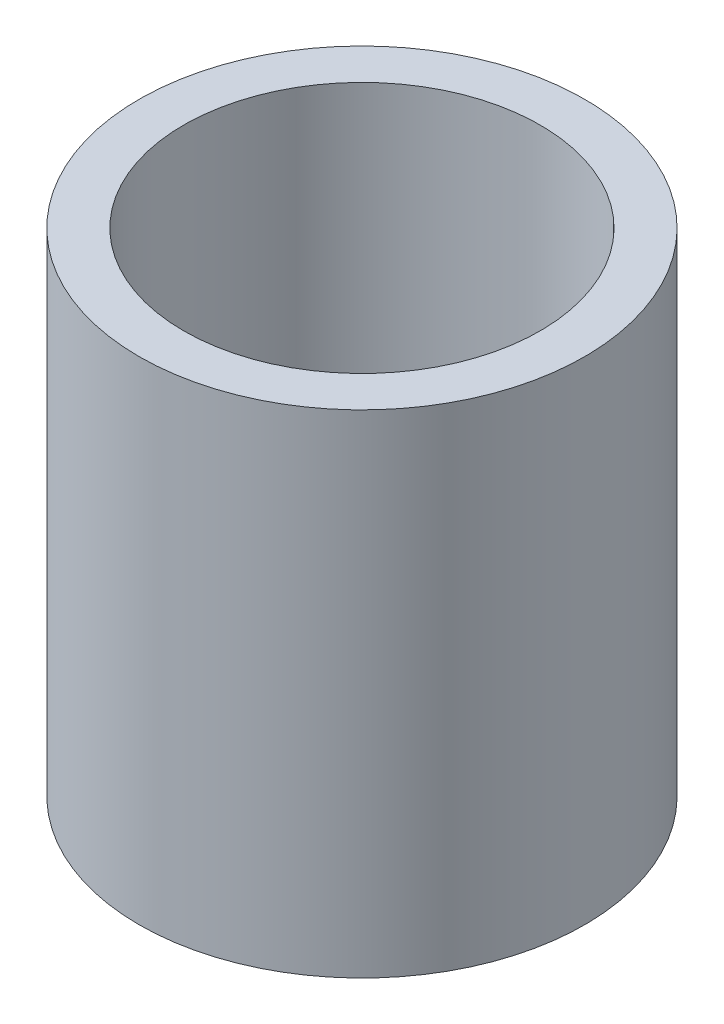
SolidWorks part; units mm, degrees
ref_plane "Front Plane" through (0, 0, 0) normal (0, 0, 1) x (1, 0, 0)
ref_plane "Top Plane" through (0, 0, 0) normal (0, 1, 0) x (1, 0, 0)
ref_plane "Right Plane" through (0, 0, 0) normal (1, 0, 0) x (0, 0, -1)
sketch "Sketch1" plane through (0, 0, 0) normal (0, 1, 0) x (1, 0, 0)
  circle A0 centre (0, 0) radius 0.625
  circle A1 centre (0, 0) radius 0.5
  dimension "D1" = 1.25
  dimension "D2" = 1
extrude "Boss-Extrude1" add sketch "Sketch1" along normal mid plane 1.38
